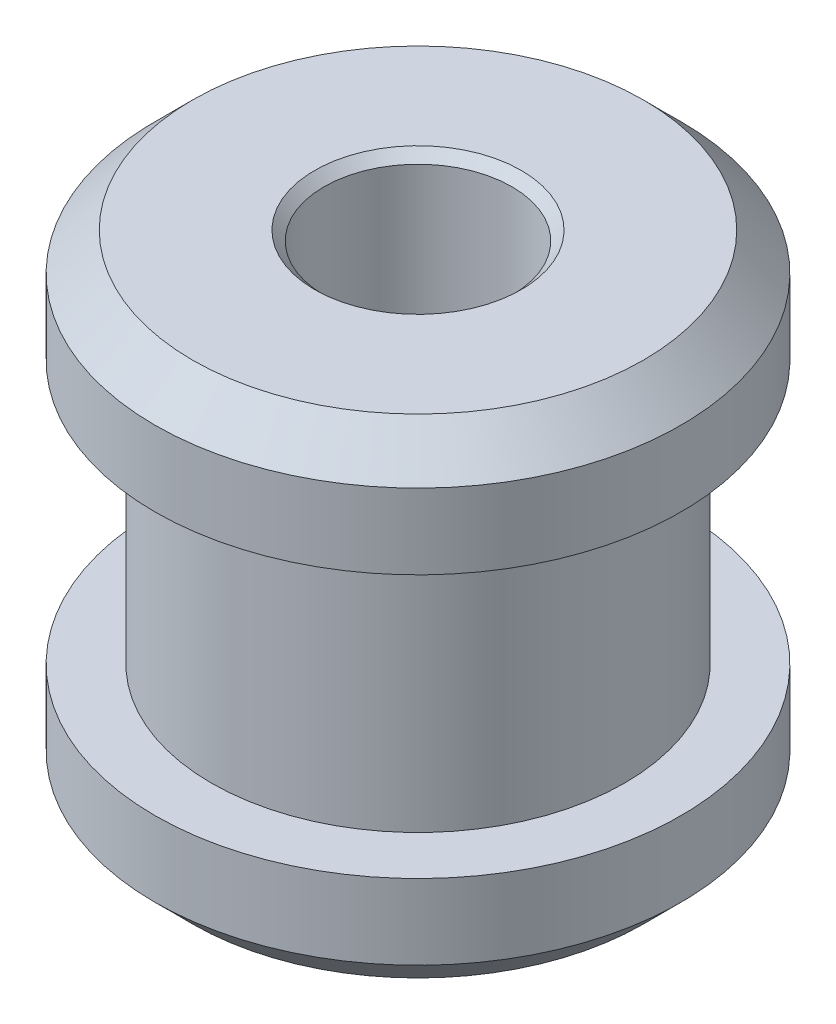
SolidWorks part; units mm, degrees
ref_plane "Front" through (0, 0, 0) normal (0, 0, 1) x (1, 0, 0)
ref_plane "Top" through (0, 0, 0) normal (0, 1, 0) x (1, 0, 0)
ref_plane "Right" through (0, 0, 0) normal (1, 0, 0) x (0, 0, -1)
ref_plane "Plane1" through (0, 3.5, 0) normal (0, -1, 0) x (1, 0, 0)
sketch "Sketch2" plane through (0, 0, 0) normal (0, -1, 0) x (1, 0, 0)
  circle A0 centre (0, 0) radius 5.5
  dimension "D1" = 11
extrude "Boss-Extrude2" add sketch "Sketch2" along normal mid plane 7
ref_plane "Plane2" through (0, -3.5, 0) normal (0, 1, 0) x (1, 0, 0)
sketch "Sketch3" plane through (0, -3.5, 0) normal (0, 1, 0) x (1, 0, 0)
  circle A0 centre (0, 0) radius 7
  dimension "D1" = 14
extrude "Boss-Extrude3" add sketch "Sketch3" against normal blind 3
chamfer "Chamfer1" distance 1 angle 45 1 edges at (0, -6.5, -7)
mirror "Mirror1" about plane through (0, 0, 0) normal (0, 1, 0) of "Chamfer1", "Boss-Extrude3"
sketch "Sketch4" plane through (0, 0, 0) normal (0, 1, 0) x (-1, 0, 0)
  circle A0 centre (0, 0) radius 2.5
  dimension "D1" = 5
extrude "Cut-Extrude1" cut sketch "Sketch4" against normal through all both and the other way through all
chamfer "Chamfer2" distance 0.25 angle 45 2 edges at (0, -6.5, -2.5) (0, 6.5, -2.5)
